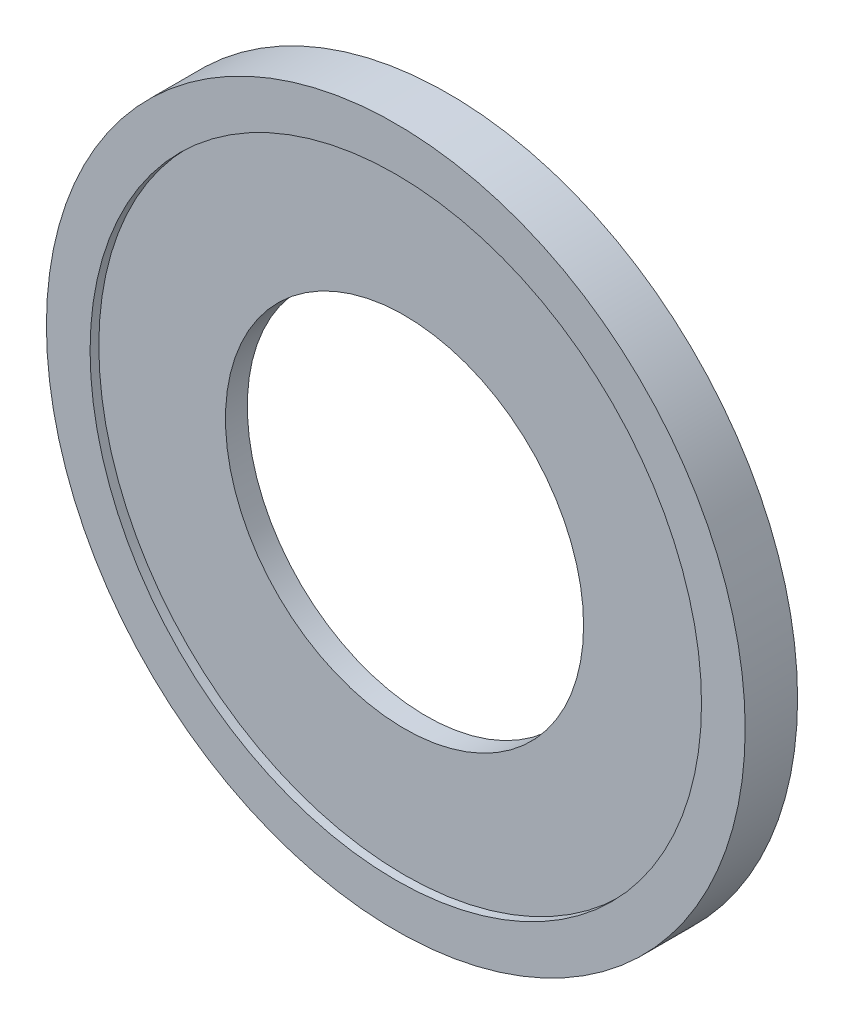
SolidWorks part; units mm, degrees
material "7075-T6 (SN)"
ref_plane "Front Plane" through (0, 0, 0) normal (0, 0, 1) x (1, 0, 0)
ref_plane "Top Plane" through (0, 0, 0) normal (0, 1, 0) x (1, 0, 0)
ref_plane "Right Plane" through (0, 0, 0) normal (1, 0, 0) x (0, 0, -1)
sketch "Sketch1" plane through (0, 0, 0) normal (0, 0, 1) x (1, 0, 0)
  circle A0 centre (0, 0) radius 8
  circle A1 centre (0, 0) radius 4.1
extrude "Outer_Flange_Contact_Annulus_ID8p2" add sketch "Sketch1" along normal blind 0.5 from offset 3
sketch "Sketch2" plane through (0, 0, 0) normal (0, 0, 1) x (1, 0, 0)
  circle A0 centre (0, 0) radius 8
  circle A1 centre (0, 0) radius 7
extrude "M14x0p5_Internal_Thread_Envelope" add sketch "Sketch2" along normal blind 1.2 from offset 2.5
